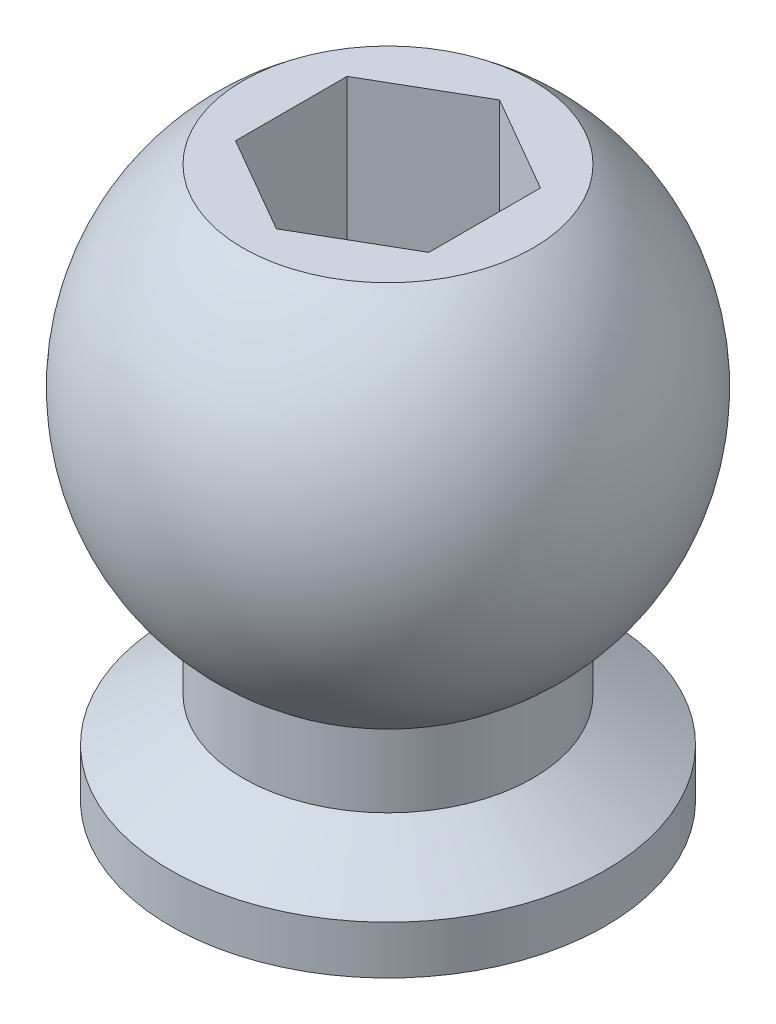
SolidWorks part; units mm, degrees
ref_plane "Front Plane" through (0, 0, 0) normal (0, 0, 1) x (1, 0, 0)
ref_plane "Top Plane" through (0, 0, 0) normal (0, 1, 0) x (1, 0, 0)
ref_plane "Right Plane" through (0, 0, 0) normal (1, 0, 0) x (0, 0, -1)
sketch "Sketch1" plane through (0, 0, 0) normal (0, 0, 1) x (1, 0, 0)
  line L0 (0, 0) -> (0, 5.7)
  line L1 (0, 5.7) -> (-1.5, 5.7)
  line L2 (-2.25, 0) -> (-2.25, 0.5)
  line L3 (0, 0) -> (-2.25, 0)
  line L4 (-2.25, 0.5) -> (-1.5, 0.95)
  line L5 (-1.5, 0.95) -> (-1.5, 1.7)
  arc A0 (-1.5, 5.7) -> (-1.5, 1.7) centre (0, 3.7) ccw
  dimension "D2" = 2.5
  dimension "D1" = 5.7
  dimension "D3" = 2
  dimension "D4" = 0.75
  dimension "D5" = 2.25
  dimension "D6" = 1.5
  dimension "D7" = 0.5
revolve "Revolve1" add sketch "Sketch1" angle 360 about L0
ref_point "Point1"
sketch "Sketch2" plane through (0, 5.7, 0) normal (0, 1, 0) x (1, 0, 0)
  line L0 (-1, -0.5774) -> (-1, 0.5774)
  line L1 (-1, 0.5774) -> (0, 1.1547)
  line L2 (0, 1.1547) -> (1, 0.5774)
  line L3 (1, 0.5774) -> (1, -0.5774)
  line L4 (1, -0.5774) -> (0, -1.1547)
  line L5 (0, -1.1547) -> (-1, -0.5774)
  line L6 (0, -1.1547) -> (0, 1.1547) construction
  line L7 (-1, 0.5774) -> (1, -0.5774) construction
  point P7 (0, 0)
  dimension "D1" = 60
  dimension "D2" = 2
extrude "Cut-Extrude1" cut sketch "Sketch2" against normal blind 2.54
hole_wizard "M2 Tapped Hole1" positions "Sketch3" profile "Sketch4" tap size "M2" standard "DIN" end condition through all
sketch "Sketch3" plane through (0, 0, 0) normal (0, -1, 0) x (-1, 0, 0)
  point P0 (0, 0)
sketch "Sketch4" plane through (0, 0, 0) normal (1, 0, 0) x (0, 0, -1)
  line L0 (0, 0) -> (0, 5.7)
  line L1 (0, 5.7) -> (0.8, 5.7)
  line L2 (0.8, 5.7) -> (0.8, 0)
  line L5 (0.8, 0) -> (0, 0)
  line L11 (0, -6.35) -> (0, 107.95) construction
  dimension "Thru Tap Drill Dia." = 1.6
  dimension "Thru Tap Drill Depth" = 5.7
cosmetic thread "Hole Thread1" parameters "D2"=2
